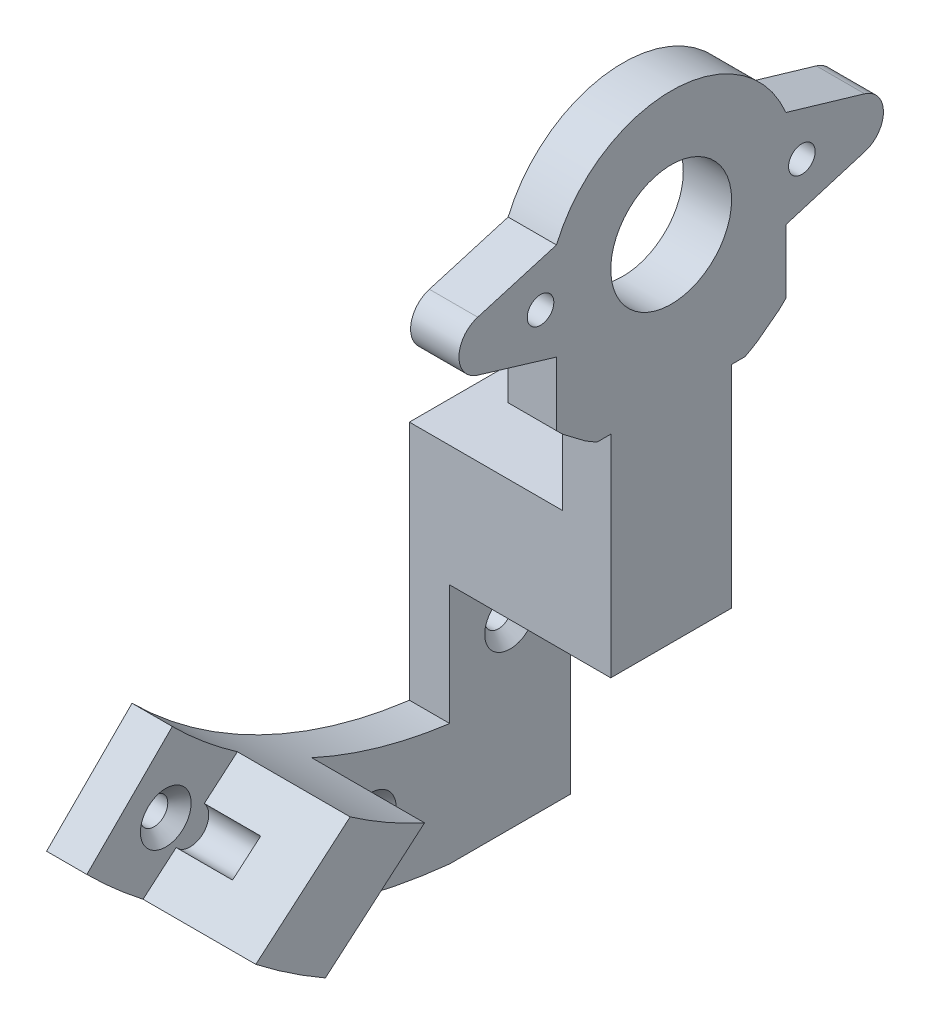
SolidWorks part; units mm, degrees
material "ABS"
ref_plane "Front Plane" through (0, 0, 0) normal (0, 0, 1) x (1, 0, 0)
ref_plane "Top Plane" through (0, 0, 0) normal (0, 1, 0) x (1, 0, 0)
ref_plane "Right Plane" through (0, 0, 0) normal (1, 0, 0) x (0, 0, -1)
sketch "Sketch1" plane through (0, 0, 0) normal (1, 0, 0) x (0, 0, -1)
  line L0 (-52.538, -1.1175) -> (-41.9314, 9.4891)
  line L1 (-7.5, 22.5) -> (7.5, 22.5)
  line L2 (-7.5, 22.5) -> (-7.5, -22.5)
  line L3 (-7.5, -22.5) -> (7.5, -22.5)
  line L4 (7.5, 22.5) -> (7.5, -22.5)
  line L5 (-7.5, 22.5) -> (7.5, -22.5) construction
  line L6 (-7.5, -22.5) -> (7.5, 22.5) construction
  line L7 (-45.5654, -7.2676) -> (-33.857, 2.7359)
  arc A2 (-7.5, -22.5) -> (-45.5654, -7.2676) centre (0, 51.4205) cw
  arc A3 (-7.5, -7.4033) -> (-41.9314, 9.4891) centre (0, 51.4205) cw
  arc A4 (-45.5654, -7.2676) -> (-52.538, -1.1175) centre (0, 51.4205) cw
  point P0 (0, 0)
  dimension "D3" = 74.3
  dimension "D4" = 45
  dimension "D7" = 15
  dimension "D1" = 15
  dimension "D2" = 45
  dimension "D5" = 41
  dimension "D6" = 49.49
extrude "Boss-Extrude1" add sketch "Sketch1" along normal blind 5
sketch "Sketch2" plane through (5, 0, 0) normal (1, 0, 0) x (0, 0, -1)
  line L0 (-45.5632, -7.2692) -> (-33.8547, 2.7343)
  line L1 (-36.934, -13.0494) -> (-24.6189, -2.5276)
  line L2 (7.5, 22.5) -> (7.5, -22.5) construction
  line L3 (-7.5, 22.5) -> (7.5, 22.5)
  line L4 (-7.5, 22.5) -> (-7.5, 7.5)
  line L5 (-7.5, 7.5) -> (7.5, 7.5)
  line L6 (7.5, 22.5) -> (7.5, 7.5)
  line L7 (-45.5654, -7.2676) -> (-33.857, 2.7359) construction
  arc A0 (-33.8547, 2.7343) -> (-24.6189, -2.5276) centre (0, 51.4205) ccw
  arc A1 (-45.5632, -7.2692) -> (-36.934, -13.0494) centre (0, 51.4205) ccw
  arc A2 (-41.9314, 9.4891) -> (-7.5, -7.4033) centre (0, 51.4205) ccw construction
  arc A3 (-52.538, -1.1175) -> (-7.5, -22.5) centre (0, 51.4205) ccw construction
  dimension "D1" = 10
  dimension "D2" = 33.8547
extrude "Boss-Extrude2" add sketch "Sketch2" along normal blind 14
sketch "Sketch3" plane through (5, 0, 0) normal (1, 0, 0) x (0, 0, -1)
  line L0 (-33.8547, 2.7343) -> (-45.5632, -7.2692) construction
  circle A0 centre (-39.709, -2.2675) radius 2.3
  dimension "D1" = 4.6
extrude "Cut-Extrude1" cut sketch "Sketch3" along normal blind 7
sketch "Sketch4" plane through (19, 0, 0) normal (1, 0, 0) x (0, 0, -1)
  line L0 (7.5, 22.5) -> (-7.5, 22.5) construction
  line L1 (7.5, 7.5) -> (7.5, 22.5) construction
  line L2 (-7.5, 7.5) -> (7.5, 7.5)
  line L3 (-7.5, 7.5) -> (-7.5, 51.42)
  line L4 (-7.5, 51.42) -> (7.5, 51.42)
  line L5 (7.5, 7.5) -> (7.5, 51.42)
  line L6 (10.6838, 34.5699) -> (13.3056, 36.5529)
  line L7 (-10.6838, 34.5699) -> (-13.3056, 36.5529)
  line L22 (-14.2413, 57.4149) -> (-24.0176, 54.5378)
  line L23 (-2.2936, 65.2898) -> (-2.2936, 66.7005)
  line L24 (2.2936, 65.2898) -> (-2.2936, 65.2898)
  line L25 (2.2936, 66.7005) -> (2.2936, 65.2898)
  line L26 (24.0176, 54.5378) -> (14.2413, 57.4149)
  line L27 (14.2516, 45.3642) -> (24.0363, 48.3078)
  line L28 (14.2516, 37.4572) -> (14.2516, 45.3642)
  line L29 (12.2999, 37.8825) -> (13.3056, 36.5529)
  line L30 (9.6781, 35.8995) -> (12.2999, 37.8825)
  line L31 (10.6838, 34.5699) -> (9.6781, 35.8995)
  line L32 (-9.165, 33.698) -> (9.165, 33.698)
  line L33 (-9.6781, 35.8995) -> (-10.6838, 34.5699)
  line L34 (-12.2999, 37.8825) -> (-9.6781, 35.8995)
  line L35 (-13.3056, 36.5529) -> (-12.2999, 37.8825)
  line L36 (-14.2516, 45.3642) -> (-14.2516, 37.4572)
  line L37 (-24.0363, 48.3078) -> (-14.2516, 45.3642)
  line L38 (-14.2413, 57.4149) -> (-24.0176, 54.5378)
  line L42 (24.0176, 54.5378) -> (14.2413, 57.4149)
  line L43 (14.2516, 45.3642) -> (24.0363, 48.3078)
  line L44 (14.2516, 37.4572) -> (14.2516, 45.3642)
  line L48 (-9.165, 33.698) -> (9.165, 33.698)
  line L52 (-14.2516, 45.3642) -> (-14.2516, 37.4572)
  line L53 (-24.0363, 48.3078) -> (-14.2516, 45.3642)
  circle A0 centre (0, 51.42) radius 12.7
  circle A1 centre (0, 51.42) radius 7.5
  arc A2 (-2.2936, 66.7005) -> (2.2936, 66.7005) centre (0, 51.42) cw
  circle A3 centre (16.22, 51.42) radius 1.5 construction
  circle A4 centre (-16.22, 51.42) radius 1.5 construction
  circle A5 centre (16.22, 51.42) radius 1.5 construction
  circle A6 centre (-16.22, 51.42) radius 1.5 construction
  circle A7 centre (-16.22, 51.42) radius 1.65
  circle A8 centre (16.22, 51.42) radius 1.65
  arc A10 (-2.2936, 66.7005) -> (-14.2413, 57.4149) centre (0, 51.42) ccw
  arc A11 (14.2413, 57.4149) -> (2.2936, 66.7005) centre (0, 51.42) ccw
  arc A12 (24.0363, 48.3078) -> (24.0176, 54.5378) centre (23.1, 51.42) ccw
  arc A13 (13.3056, 36.5529) -> (14.2516, 37.4572) centre (0, 51.42) ccw
  arc A14 (9.165, 33.698) -> (10.6838, 34.5699) centre (0, 51.42) ccw
  arc A15 (-10.6838, 34.5699) -> (-9.165, 33.698) centre (0, 51.42) ccw
  arc A16 (-14.2516, 37.4572) -> (-13.3056, 36.5529) centre (0, 51.42) ccw
  arc A17 (-24.0176, 54.5378) -> (-24.0363, 48.3078) centre (-23.1, 51.42) ccw
  arc A18 (-2.2936, 66.7005) -> (-14.2413, 57.4149) centre (0, 51.42) ccw
  arc A19 (14.2413, 57.4149) -> (2.2936, 66.7005) centre (0, 51.42) ccw
  arc A20 (24.0363, 48.3078) -> (24.0176, 54.5378) centre (23.1, 51.42) ccw
  arc A21 (13.3056, 36.5529) -> (14.2516, 37.4572) centre (0, 51.42) ccw
  arc A22 (9.165, 33.698) -> (10.6838, 34.5699) centre (0, 51.42) ccw
  arc A23 (-10.6838, 34.5699) -> (-9.165, 33.698) centre (0, 51.42) ccw
  arc A24 (-14.2516, 37.4572) -> (-13.3056, 36.5529) centre (0, 51.42) ccw
  arc A25 (-24.0176, 54.5378) -> (-24.0363, 48.3078) centre (-23.1, 51.42) ccw
  line M6 (-7.5, 22.5) -> (-7.5, 7.5)
  line M7 (-7.5, 7.5) -> (7.5, 7.5)
  line M8 (7.5, 7.5) -> (7.5, 22.5)
  line M9 (7.5, 22.5) -> (-7.5, 22.5)
  dimension "D2" = 25.4
  dimension "D3" = 15
  dimension "D5" = 3.3
  dimension "D1" = 28.92
  dimension "D4" = 0
extrude "Boss-Extrude3" add sketch "Sketch4" along normal blind 6 contours M9 M6 M7 M8 | L48 L3 L5 M9 | A0 L3 L48 L5 | L38 A25 L53 L52 A24 L7 A23 L48 L3 A0 L5 A22 L6 A21 L44 L43 A20 L42 A19 A2 A18 | A1 L3 A0 L5 | A1 L5 A0 L3
hole_wizard "CSK for M3 Flat Head Machine Screw1" positions "Sketch6" profile "Sketch7" countersink size "M3" standard "ANSI Metric"
sketch "Sketch6" plane through (5, 0, 0) normal (1, 0, 0) x (0, 0, -1)
  line L3 (-19.2301, -20.3478) -> (-15.3478, -5.8589) construction
  line L4 (-7.5, 7.5) -> (-7.5, -7.4033) construction
  line L5 (-7.5, 7.5) -> (7.5, 7.5) construction
  arc A0 (-24.6189, -2.5276) -> (-7.5, -7.4033) centre (0, 51.4205) ccw construction
  arc A1 (-36.934, -13.0494) -> (-7.5, -22.5) centre (0, 51.4205) ccw construction
  point P0 (-42.7434, 0.0904)
  point P2 (-17.289, -13.1034)
  point P4 (0, 0)
  point P42 (-17.289, -13.1034)
  point P52 (0, 51.42)
  dimension "D2" = 15
  dimension "D4" = 35.2434
  dimension "D5" = 7.4096
sketch "Sketch7" plane through (5, 0.0904, 42.7434) normal (0, 1, 0) x (0, 0, -1)
  line L0 (0, 0) -> (0, 7.3715)
  line L1 (0, 7.3715) -> (1.7, 6.35)
  line L2 (1.7, 6.35) -> (1.7, 1.45)
  line L3 (1.7, 1.45) -> (3.15, 0)
  line L5 (3.15, 0) -> (0, 0)
  line L6 (-1.7, 1.45) -> (-3.15, 0) construction
  line L10 (0, 7.3715) -> (-1.7, 6.35) construction
  line L11 (0, -6.35) -> (0, 107.95) construction
  dimension "Hole Dia." = 3.4
  dimension "Hole Depth" = 6.35
  dimension "Near C'Sink Dia." = 6.3
  dimension "Near C'Sink Angle" = 90
  dimension "Drill Angle" = 118
